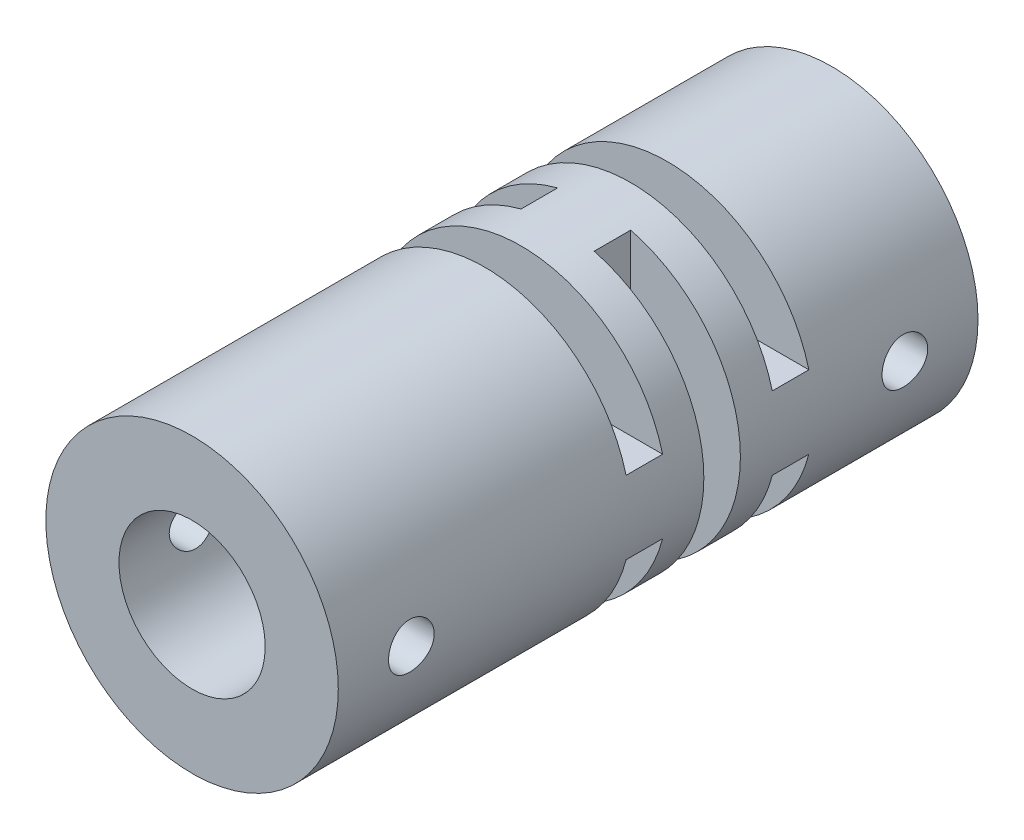
SolidWorks part; units mm, degrees
material "POM generico"
ref_plane "Piano frontale" through (0, 0, 0) normal (0, 0, 1) x (1, 0, 0)
ref_plane "Piano superiore" through (0, 0, 0) normal (0, 1, 0) x (1, 0, 0)
ref_plane "Piano destro" through (0, 0, 0) normal (1, 0, 0) x (0, 0, -1)
sketch "Schizzo1" plane through (0, 0, 0) normal (0, 0, 1) x (1, 0, 0)
  circle A0 centre (0, 0) radius 8
  dimension "D1" = 16
extrude "Estrusione-Estrusione1" add sketch "Schizzo1" along normal blind 35
sketch "Schizzo2" plane through (0, 0, 35) normal (0, 0, 1) x (1, 0, 0)
  circle A0 centre (0, 0) radius 2.5
extrude "Taglio-Estrusione1" cut sketch "Schizzo2" against normal through all
sketch "Schizzo3" plane through (0, 0, 35) normal (0, 0, 1) x (1, 0, 0)
  circle A0 centre (0, 0) radius 4
  dimension "D1" = 8
extrude "Taglio-Estrusione2" cut sketch "Schizzo3" against normal blind 15
sketch "Schizzo4" plane through (0, 0, 0) normal (1, 0, 0) x (0, 0, -1)
  line L0 (-35, 8) -> (-35, -8) construction
  line L1 (0, -8) -> (0, 8) construction
  circle A0 centre (-31, 0) radius 1.25
  circle A1 centre (-4, 0) radius 1.25
  dimension "D3" = 2.5
  dimension "D4" = 2.5
  dimension "D1" = 4
  dimension "D2" = 4
extrude "Taglio-Estrusione3" cut sketch "Schizzo4" against normal through all and the other way through all
ref_plane "Piano2" through (0, -8, 0) normal (0, 1, 0) x (1, 0, 0)
ref_plane "Piano3" through (0, 8, 0) normal (0, 1, 0) x (1, 0, 0)
sketch "Schizzo13" plane through (0, 0, 0) normal (1, 0, 0) x (0, 0, -1)
  line L0 (8.8, 8) -> (-8.8, 8) construction
  line L1 (-19, 8) -> (-17, 8)
  line L2 (-19, 8) -> (-19, 2)
  line L3 (-19, 2) -> (-17, 2)
  line L4 (-17, 8) -> (-17, 2)
  line L5 (8.8, -8) -> (-8.8, -8) construction
  line L6 (-11, 8) -> (-9, 8)
  line L7 (-11, 8) -> (-11, 2)
  line L8 (-11, 2) -> (-9, 2)
  line L9 (-9, 8) -> (-9, 2)
  line L10 (-19, -8) -> (-17, -8)
  line L11 (-19, -8) -> (-19, -2)
  line L12 (-19, -2) -> (-17, -2)
  line L13 (-17, -8) -> (-17, -2)
  line L14 (-35, 8) -> (-35, -8) construction
  line L15 (-11, -8) -> (-9, -8)
  line L16 (-11, -8) -> (-11, -2)
  line L17 (-11, -2) -> (-9, -2)
  line L18 (-9, -8) -> (-9, -2)
  dimension "D1" = 2
  dimension "D2" = 16
  dimension "D3" = 6
  dimension "D4" = 6
extrude "Taglio-Estrusione8" cut sketch "Schizzo13" against normal up to next and the other way up to next
sketch "Schizzo14" plane through (0, 0, 0) normal (0, 1, 0) x (1, 0, 0)
  line L0 (-8, -5.25) -> (-8, -29.75) construction
  line L1 (-8, -13) -> (-2, -13)
  line L2 (-8, -13) -> (-8, -15)
  line L3 (-8, -15) -> (-2, -15)
  line L4 (-2, -13) -> (-2, -15)
  line L5 (8, -29.75) -> (8, -5.25) construction
  line L6 (8, -13) -> (2, -13)
  line L7 (8, -13) -> (8, -15)
  line L8 (8, -15) -> (2, -15)
  line L9 (2, -13) -> (2, -15)
  line L10 (7.746, -11) -> (-7.746, -11) construction
  dimension "D1" = 6
  dimension "D2" = 2
  dimension "D3" = 2
extrude "Taglio-Estrusione9" cut sketch "Schizzo14" against normal up to next and the other way up to next
